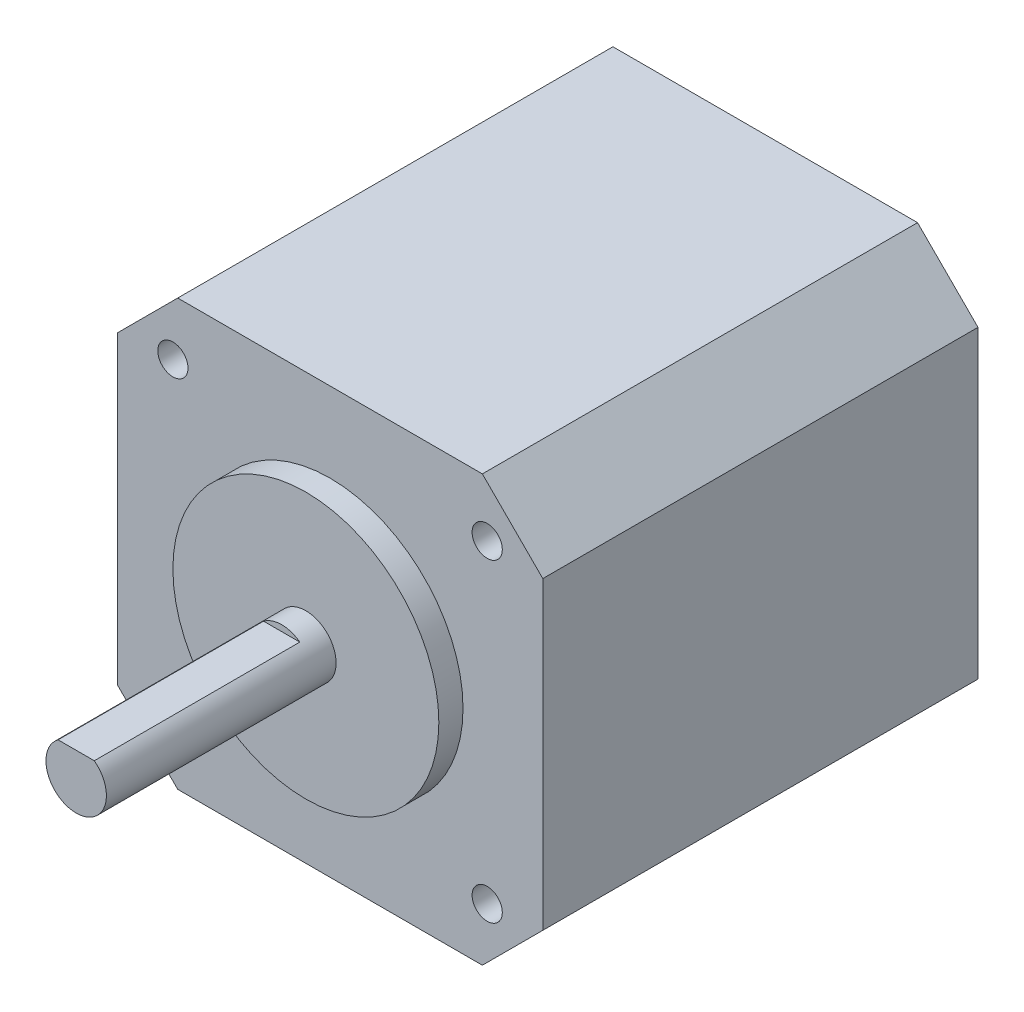
SolidWorks part; units mm, degrees
ref_plane "Front Plane" through (0, 0, 0) normal (0, 0, 1) x (1, 0, 0)
ref_plane "Top Plane" through (0, 0, 0) normal (0, 1, 0) x (1, 0, 0)
ref_plane "Right Plane" through (0, 0, 0) normal (1, 0, 0) x (0, 0, -1)
sketch "Sketch1" plane through (0, 0, 0) normal (0, 0, 1) x (1, 0, 0)
  line L1 (-17.6, -17.6) -> (17.6, -17.6)
  line L2 (-17.6, -17.6) -> (-17.6, 17.6)
  line L3 (-17.6, 17.6) -> (17.6, 17.6)
  line L4 (17.6, -17.6) -> (17.6, 17.6)
  dimension "D1" = 35.2
  dimension "D2" = 17.6
  dimension "D3" = 17.6
extrude "Boss-Extrude1" add sketch "Sketch1" along normal blind 36
sketch "Sketch2" plane through (0, 0, 36) normal (0, 0, 1) x (1, 0, 0)
  circle A0 centre (0, 0) radius 11
  dimension "D1" = 22
extrude "Boss-Extrude2" add sketch "Sketch2" along normal blind 2
sketch "Sketch3" plane through (0, 0, 38) normal (0, 0, 1) x (1, 0, 0)
  circle A0 centre (0, 0) radius 2.5
  dimension "D1" = 5
extrude "Boss-Extrude3" add sketch "Sketch3" along normal blind 19
chamfer "Chamfer1" distance 5 angle 45 4 edges at (-17.6, 17.6, 18) (-17.6, -17.6, 18) (17.6, -17.6, 18) (17.6, 17.6, 18)
hole_wizard "M3x0.5 Tapped Hole1" positions "Sketch5" profile "Sketch4" tap size "M3x0.5" standard "Ansi Metric"
sketch "Sketch5" plane through (0, 0, 36) normal (0, 0, 1) x (1, 0, 0)
  point P0 (13, 13)
  dimension "D1" = 13
  dimension "D2" = 13
sketch "Sketch4" plane through (13, 13, 36) normal (1, 0, 0) x (0, -1, 0)
  line L0 (0, 0) -> (0, 6.2511)
  line L1 (0, 6.2511) -> (1.25, 5.5)
  line L2 (1.25, 5.5) -> (1.25, 0)
  line L5 (1.25, 0) -> (0, 0)
  line L10 (0, 6.2511) -> (-1.25, 5.5) construction
  line L11 (0, -6.35) -> (0, 107.95) construction
  dimension "Tap Drill Dia." = 2.5
  dimension "Tap Drill Depth" = 5.5
  dimension "Drill Angle" = 118
cosmetic thread "Hole Thread1" parameters "D1"=4, "D2"=3
pattern_circular "CirPattern1" count 4 over 360 about axis through (0, 0, 0) along (0, 0, 1) of "M3x0.5 Tapped Hole1"
sketch "Sketch6" plane through (0, 0, 57) normal (0, 0, 1) x (1, 0, 0)
  line L1 (-2.3815, 3.3386) -> (2.1215, 3.3386)
  line L2 (-2.3815, 3.3386) -> (-2.3815, 2)
  line L3 (-2.3815, 2) -> (2.1215, 2)
  line L4 (2.1215, 3.3386) -> (2.1215, 2)
  circle A0 centre (0, 0) radius 2.5 construction
  dimension "D1" = 2
extrude "Cut-Extrude1" cut sketch "Sketch6" against normal offset from surface (17 mm away) 2 up to face at (11, 0, 38)
ref_plane "Plane1" through (0, 0, 18) normal (0, 0, -1) x (-1, 0, 0)
mirror "Mirror1" about plane through (0, 0, 18) normal (0, 0, -1) of "CirPattern1", "M3x0.5 Tapped Hole1"
